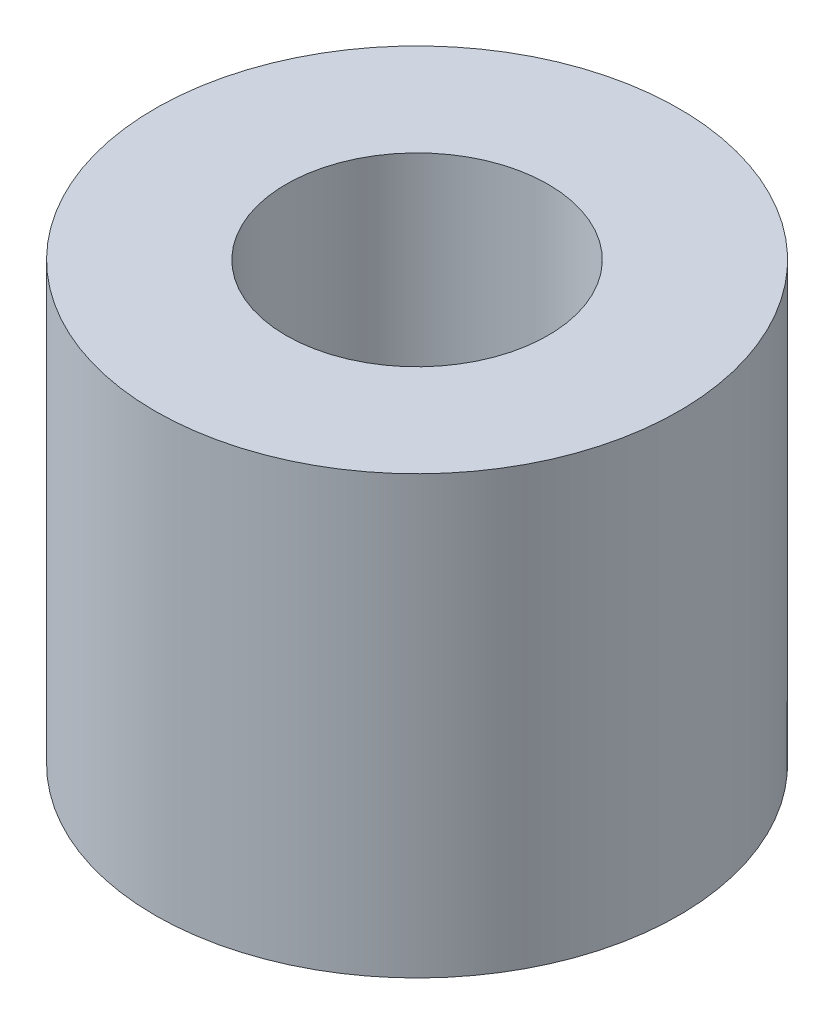
SolidWorks part; units mm, degrees
ref_plane "Plano frontal" through (0, 0, 0) normal (0, 0, 1) x (1, 0, 0)
ref_plane "Plano superior" through (0, 0, 0) normal (0, 1, 0) x (1, 0, 0)
ref_plane "Plano direito" through (0, 0, 0) normal (1, 0, 0) x (0, 0, -1)
sketch "Esboço1" plane through (0, 0, 0) normal (0, 1, 0) x (1, 0, 0)
  circle A0 centre (0, 0) radius 3
  circle A1 centre (0, 0) radius 1.5
  dimension "D1" = 6
  dimension "D2" = 3
extrude "Ressalto-extrusão1" add sketch "Esboço1" along normal blind 5
